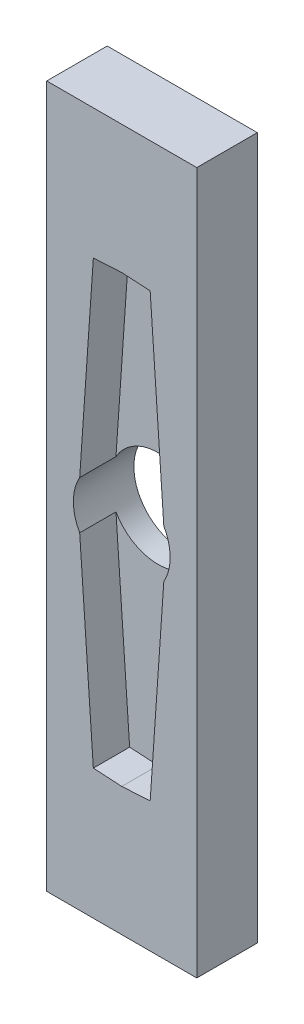
SolidWorks part; units mm, degrees
ref_plane "Front Plane" through (0, 0, 0) normal (0, 0, 1) x (1, 0, 0)
ref_plane "Top Plane" through (0, 0, 0) normal (0, 1, 0) x (1, 0, 0)
ref_plane "Right Plane" through (0, 0, 0) normal (1, 0, 0) x (0, 0, -1)
sketch "Sketch1" plane through (0, 0, 0) normal (0, 0, 1) x (1, 0, 0)
  line L1 (6.2, -29) -> (-6.2, -29)
  line L2 (6.2, -29) -> (6.2, 29)
  line L3 (6.2, 29) -> (-6.2, 29)
  line L4 (-6.2, -29) -> (-6.2, 29)
  line L5 (6.2, -29) -> (-6.2, 29) construction
  line L6 (6.2, 29) -> (-6.2, -29) construction
  point P0 (0, 0)
  dimension "D1" = 58
  dimension "D2" = 12.4
extrude "Boss-Extrude1" add sketch "Sketch1" against normal blind 5
sketch "Sketch2" plane through (0, 0, 0) normal (0, 0, 1) x (1, 0, 0)
  line L2 (0, 0) -> (9.4422, 0) construction
  line L7 (-3.6138, 0) -> (-2.3482, 18.2538)
  line L8 (0, 18.3878) -> (-2.3482, 18.2538)
  line L9 (0, 0) -> (0, 19.7752) construction
  line L10 (3.6138, 0) -> (2.3482, 18.2538)
  line L11 (0, 18.3878) -> (2.3482, 18.2538)
  line L12 (0, -18.3878) -> (2.3482, -18.2538)
  line L13 (3.6138, 0) -> (2.3482, -18.2538)
  line L14 (0, -18.3878) -> (-2.3482, -18.2538)
  line L15 (-3.6138, 0) -> (-2.3482, -18.2538)
extrude "Cut-Extrude1" cut sketch "Sketch2" against normal blind 3
sketch "Sketch4" plane through (0, 0, 0) normal (0, 0, 1) x (1, 0, 0)
  circle A0 centre (0, 0) radius 4
  dimension "D1" = 8
extrude "Cut-Extrude2" cut sketch "Sketch4" against normal blind 5
